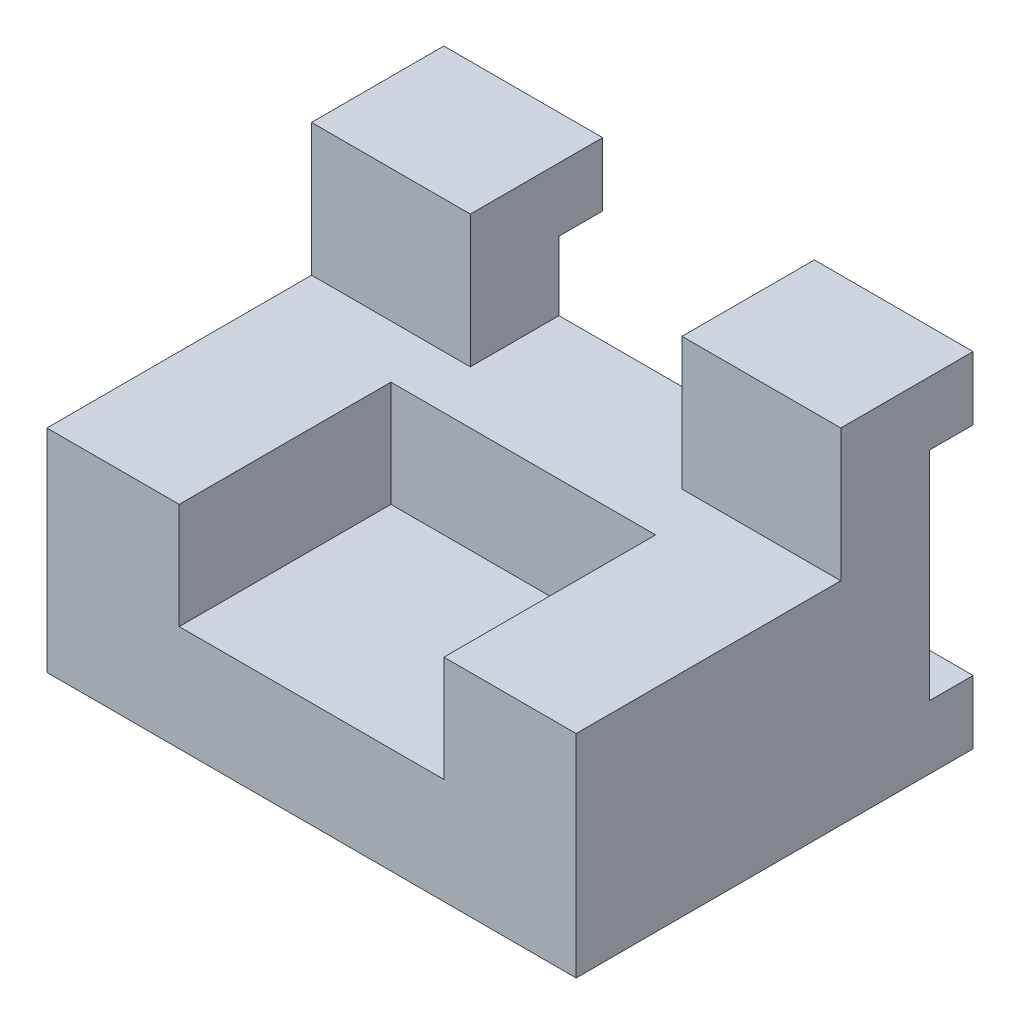
SolidWorks part; units mm, degrees
ref_plane "Front Plane" through (0, 0, 0) normal (0, 0, 1) x (1, 0, 0)
ref_plane "Top Plane" through (0, 0, 0) normal (0, 1, 0) x (1, 0, 0)
ref_plane "Right Plane" through (0, 0, 0) normal (1, 0, 0) x (0, 0, -1)
sketch "Sketch1" plane through (0, 0, 0) normal (0, 0, 1) x (1, 0, 0)
  line L1 (0, 0) -> (100, 0)
  line L2 (0, 0) -> (0, 65)
  line L3 (0, 65) -> (100, 65)
  line L4 (100, 0) -> (100, 65)
  dimension "D1" = 100
  dimension "D2" = 65
extrude "Boss-Extrude1" add sketch "Sketch1" along normal blind 25
sketch "Sketch2" plane through (100, 0, 0) normal (1, 0, 0) x (0, 0, -1)
  line L0 (0, 53) -> (-8.2326, 53)
  line L1 (0, 0) -> (0, 65) construction
  line L2 (-8.2326, 53) -> (-8.2326, 12)
  line L3 (-8.2326, 12) -> (0, 12)
  line L4 (-25, 0) -> (0, 0) construction
  line L5 (-25, 65) -> (0, 65) construction
  line L10 (0, 0) -> (0, 65)
  line L11 (0, 65) -> (-25, 65)
  line L12 (-25, 65) -> (-25, 0)
  line L13 (-25, 0) -> (0, 0)
  line L14 (0, 12) -> (0, 53)
  dimension "D1" = 41
  dimension "D2" = 12
  dimension "D3" = 12
  dimension "D4" = 0
extrude "Cut-Extrude1" cut sketch "Sketch2" against normal up to next
sketch "Sketch3" plane through (0, 65, 0) normal (0, 1, 0) x (1, 0, 0)
  line L0 (30, 0) -> (30, -25)
  line L1 (100, 0) -> (0, 0) construction
  line L2 (100, -25) -> (0, -25) construction
  line L3 (70, 0) -> (70, -25)
  line L4 (0, -25) -> (0, 0) construction
  line L5 (100, -25) -> (100, 0) construction
  line L6 (30, 0) -> (70, 0)
  line L7 (30, -25) -> (70, -25)
  dimension "D1" = 40
  dimension "D2" = 30
  dimension "D3" = 30
extrude "Cut-Extrude2" cut sketch "Sketch3" against normal blind 25
sketch "Sketch4" plane through (0, 0, 25) normal (0, 0, 1) x (1, 0, 0)
  line L0 (0, 40) -> (100, 40)
  line L1 (0, 65) -> (0, 0) construction
  line L2 (100, 0) -> (100, 65) construction
  line L3 (0, 0) -> (100, 0) construction
  line L12 (100, 65) -> (70, 65)
  line L13 (70, 65) -> (70, 40)
  line L14 (70, 40) -> (30, 40)
  line L15 (30, 40) -> (30, 65)
  line L16 (30, 65) -> (0, 65)
  line L17 (0, 65) -> (0, 0)
  line L18 (0, 0) -> (100, 0)
  line L19 (100, 0) -> (100, 65)
  line L20 (100, 65) -> (70, 65)
  line L21 (70, 65) -> (70, 40)
  line L22 (70, 40) -> (30, 40)
  line L23 (30, 40) -> (30, 65)
  line L24 (30, 65) -> (0, 65)
  line L25 (0, 65) -> (0, 40)
  line L27 (100, 40) -> (100, 65)
  line M4 (70, 40) -> (30, 40)
  line M7 (0, 65) -> (0, 0)
  line M8 (0, 0) -> (100, 0)
  line M9 (100, 0) -> (100, 65)
  dimension "D1" = 40
  dimension "D2" = 0
extrude "Boss-Extrude2" add sketch "Sketch4" along normal blind 50 contours L0 M7 M8 M9 M4
sketch "Sketch6" plane through (0, 40, 0) normal (0, 1, 0) x (1, 0, 0)
  line L0 (75, -75) -> (75, -35)
  line L1 (0, -75) -> (100, -75) construction
  line L2 (75, -35) -> (25, -35)
  line L3 (25, -35) -> (25, -75)
  line L4 (100, -75) -> (100, -25) construction
  line L5 (0, -75) -> (0, -25) construction
  dimension "D1" = 40
  dimension "D2" = 50
  dimension "D3" = 25
  dimension "D4" = 25
extrude "Cut-Extrude3" cut sketch "Sketch6" against normal blind 20 and the other way through all
